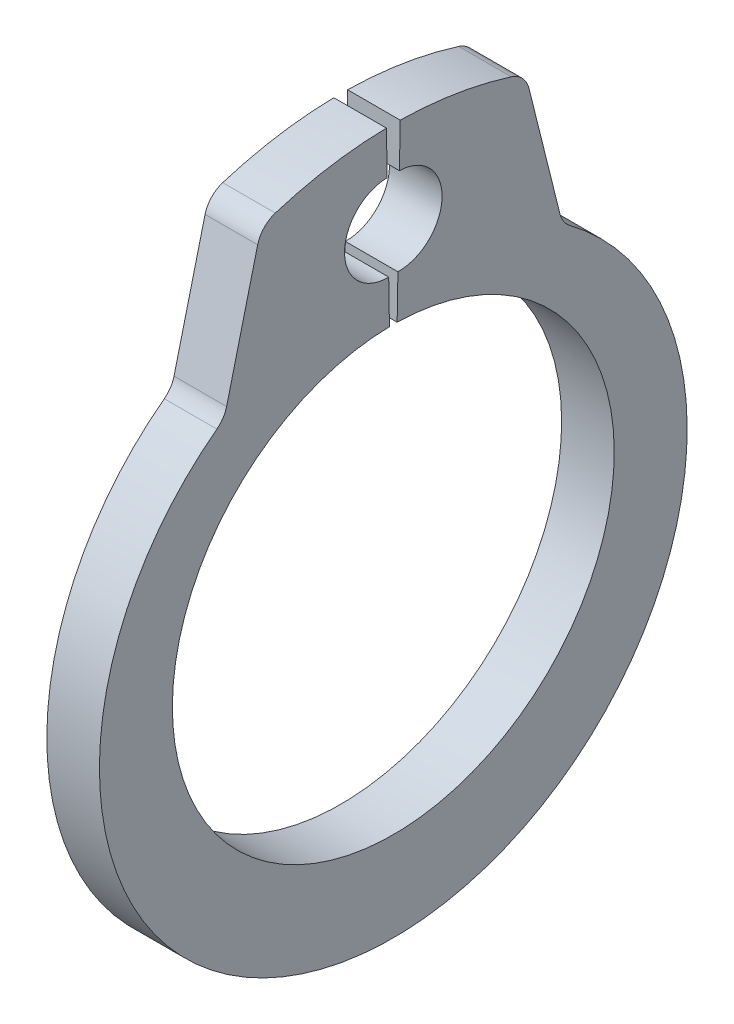
SolidWorks part; units mm, degrees
material "Cast Carbon Steel"
ref_plane "Front" through (0, 0, 0) normal (0, 0, 1) x (1, 0, 0)
ref_plane "Top" through (0, 0, 0) normal (0, 1, 0) x (1, 0, 0)
ref_plane "Right" through (0, 0, 0) normal (1, 0, 0) x (0, 0, -1)
sketch "Sketch1" plane through (0, 0, 0) normal (1, 0, 0) x (0, 0, -1)
  line L0 (0, 0) -> (0, 4.2) construction
  line L1 (-0.0733, 4.1994) -> (-0.1309, 7.4989) construction
  line L2 (-0.1309, 7.4989) -> (-2.4145, 7.459) construction
  line L3 (-2.4145, 7.459) -> (-3.2128, 4.257) construction
  line L4 (0.1309, 7.4989) -> (0.0733, 4.1994) construction
  line L5 (0.1309, 7.4989) -> (2.4145, 7.459) construction
  line L6 (2.4145, 7.459) -> (3.2128, 4.257) construction
  line L7 (-3.2128, 4.257) -> (-2.5301, 3.3524) construction
  line L8 (3.2128, 4.257) -> (2.5301, 3.3524) construction
  line L9 (0, -4.2) -> (0, -5.9) construction
  line L10 (-2.4145, 7.459) -> (-0.0733, 4.1994) construction
  line L11 (0.0733, 4.1994) -> (0.0877, 5.0242)
  line L12 (0, 4.2) -> (0, 7.5) construction
  line L13 (2.5123, 7.0667) -> (3.2128, 4.257)
  line L14 (-2.5123, 7.0667) -> (-3.2128, 4.257)
  line L16 (0.1165, 6.674) -> (0.1309, 7.4989)
  line L17 (-0.1165, 6.674) -> (-0.1309, 7.4989)
  line L18 (-0.0877, 5.0242) -> (-0.0733, 4.1994)
  circle A0 centre (0, 0) radius 4.2 construction
  arc A1 (-0.0733, 4.1994) -> (0.0733, 4.1994) centre (0, 0) ccw
  circle A2 centre (0, -0.3134) radius 5.5866 construction
  arc A3 (0.1165, 6.674) -> (0.0877, 5.0242) centre (0.1021, 5.8491) cw
  arc A4 (-0.0877, 5.0242) -> (-0.1165, 6.674) centre (-0.1021, 5.8491) cw
  arc A6 (-3.2128, 4.257) -> (3.2128, 4.257) centre (0, -0.3134) ccw
  arc A7 (0.1309, 7.4989) -> (2.5123, 7.0667) centre (0, 0) cw
  arc A8 (-0.1309, 7.4989) -> (-2.5123, 7.0667) centre (0, 0) ccw
  dimension "D1" = 75
  dimension "A" = 8.4
  dimension "D2" = 1.65
  dimension "Smin" = 1.1333
  dimension "Smax" = 1.7
  dimension "H" = 3.3
  dimension "Angle" = 1
extrude "Extrude1" add sketch "Sketch1" along normal mid plane 1
fillet "Fillet1" radius 0.5 4 edges at (0, 4.257, 3.2128) (0, 7.0667, 2.5123) (0, 7.0667, -2.5123) (0, 4.257, -3.2128)
sketch "Sketch2" plane through (0, 0, 0) normal (0, 0, 1) x (1, 0, 0)
  line L0 (-2.75, 0) -> (8.25, 0)
  line L1 (8.25, 0) -> (8.25, -4.5)
  line L2 (-0.55, -4.5) -> (-2.55, -4.5)
  line L3 (8.25, -4.5) -> (0.55, -4.5)
  line L4 (0.55, -4.5) -> (0.55, -4.3)
  line L5 (0.55, -4.3) -> (-0.55, -4.3)
  line L6 (-0.55, -4.3) -> (-0.55, -4.5)
  line L7 (-0.55, -4.5) -> (-2.75, -4.5) construction
  line L8 (-2.75, -4.5) -> (-2.75, 0) construction
  line L9 (0, -4.3) -> (0, 0) construction
  line L10 (8.25, 0) -> (14.0551, 0) construction
  line L11 (-2.55, -4.5) -> (-2.75, -4.3)
  line L12 (-2.75, -4.3) -> (-2.75, 0)
  dimension "D1" = 45
  dimension "Dg" = 8.6
  dimension "Ds" = 9
  dimension "D2" = 11
  dimension "W" = 1.1
  dimension "D3" = 2.75
revolve "Revolve1" [suppressed] add sketch "Sketch2" angle 360 about L10
equation "\"D2@Sketch2\" = \"W@Sketch2\"*10"
equation "\"D3@Sketch2\" = \"D2@Sketch2\"/4"
equation "\"Smin@Sketch1\" = \"Smax@Sketch1\"/1.5"
equation "\"D2@Sketch1\" = \"H@Sketch1\"/2"
